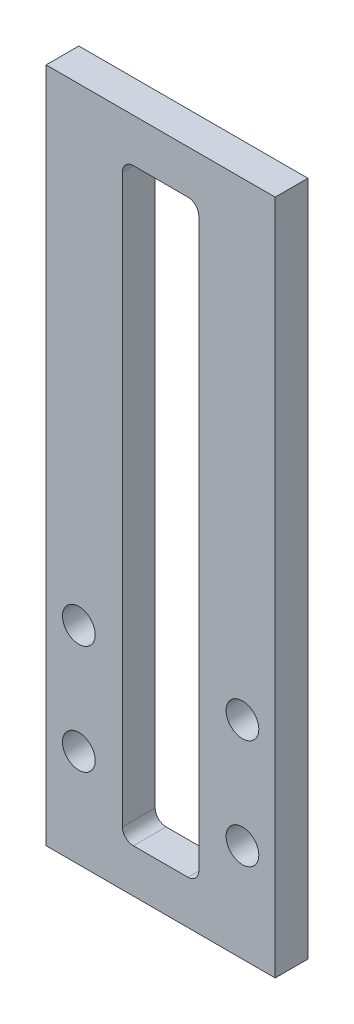
SolidWorks part; units mm, degrees
material "Thornel Mat VMA"
ref_plane "前视基准面" through (0, 0, 0) normal (0, 0, 1) x (1, 0, 0)
ref_plane "上视基准面" through (0, 0, 0) normal (0, 1, 0) x (1, 0, 0)
ref_plane "右视基准面" through (0, 0, 0) normal (1, 0, 0) x (0, 0, -1)
sketch "草图1" plane through (0, 0, 0) normal (0, 0, 1) x (1, 0, 0)
  line L0 (0, 36.2949) -> (0, -36.0138) construction
  line L1 (-40.9048, 0) -> (52.0636, 0) construction
  line L2 (10.5, -14) -> (10.5, 14) construction
  line L3 (-10.5, 14) -> (10.5, 14)
  line L4 (-10.5, 14) -> (-10.5, -14)
  line L5 (-10.5, -14) -> (10.5, -14)
  line L6 (34.5, 4) -> (34.5, -4)
  line L7 (10.5, 14) -> (10.5, 4)
  line L8 (10.5, 4) -> (34.5, 4)
  line L9 (10.5, -14) -> (10.5, -4)
  line L10 (10.5, -4) -> (34.5, -4)
  circle A0 centre (-7.5, 5) radius 1.5
  circle A1 centre (7.5, 5) radius 1.5
  circle A2 centre (-7.5, -5) radius 1.5
  circle A3 centre (7.5, -5) radius 1.5
  circle A4 centre (16.5, 0) radius 1.5
  circle A5 centre (31.5, 0) radius 1.5
  dimension "D1" = 3
  dimension "D2" = 10
  dimension "D3" = 15
  dimension "D4" = 3
  dimension "D5" = 9
  dimension "D8" = 3
  dimension "D9" = 15
  dimension "D10" = 3
  dimension "D11" = 6
  dimension "D6" = 24
  dimension "D7" = 3
  dimension "D12" = 4
  dimension "D13" = 4
extrude "凸台-拉伸1" add sketch "草图1" along normal blind 3
fillet "圆角1" radius 2 2 edges at (10.5, -4, 1.5) (10.5, 4, 1.5)
sketch "草图3" plane through (0, 0, 3) normal (0, 0, 1) x (1, 0, 0)
  line L1 (10.5, 14) -> (35.6387, 14)
  line L2 (10.5, 14) -> (10.5, -15.7039)
  line L3 (10.5, -15.7039) -> (35.6387, -15.7039)
  line L4 (35.6387, 14) -> (35.6387, -15.7039)
extrude "切除-拉伸1" cut sketch "草图3" against normal through all
sketch "草图4" plane through (0, 0, 3) normal (0, 0, 1) x (1, 0, 0)
  line L0 (10.5, -14) -> (10.5, 14) construction
  line L1 (-10.5, 14) -> (10.5, 14)
  line L2 (-10.5, 14) -> (-10.5, 48)
  line L3 (-10.5, 48) -> (10.5, 48)
  line L4 (10.5, 14) -> (10.5, 48)
  dimension "D1" = 34
extrude "凸台-拉伸2" add sketch "草图4" against normal up to surface (3 mm away) up to face at (0, 0, 0)
sketch "草图5" plane through (0, 0, 3) normal (0, 0, 1) x (1, 0, 0)
  line L0 (0, -14) -> (0, 48) construction
  line L1 (-10.5, -14) -> (10.5, -14) construction
  line L2 (10.5, 48) -> (-10.5, 48) construction
  line L4 (-3.5, 44) -> (3.5, 44)
  line L5 (-3.5, 44) -> (-3.5, -10)
  line L6 (-3.5, -10) -> (3.5, -10)
  line L7 (3.5, 44) -> (3.5, -10)
  circle A0 centre (7.5, 5) radius 1.5 construction
  dimension "D1" = 4
  dimension "D2" = 4
  dimension "D3" = 4
extrude "切除-拉伸2" cut sketch "草图5" against normal through all
fillet "圆角2" radius 1 4 edges at (3.5, -10, 1.5) (-3.5, -10, 1.5) (3.5, 44, 1.5) (-3.5, 44, 1.5)
